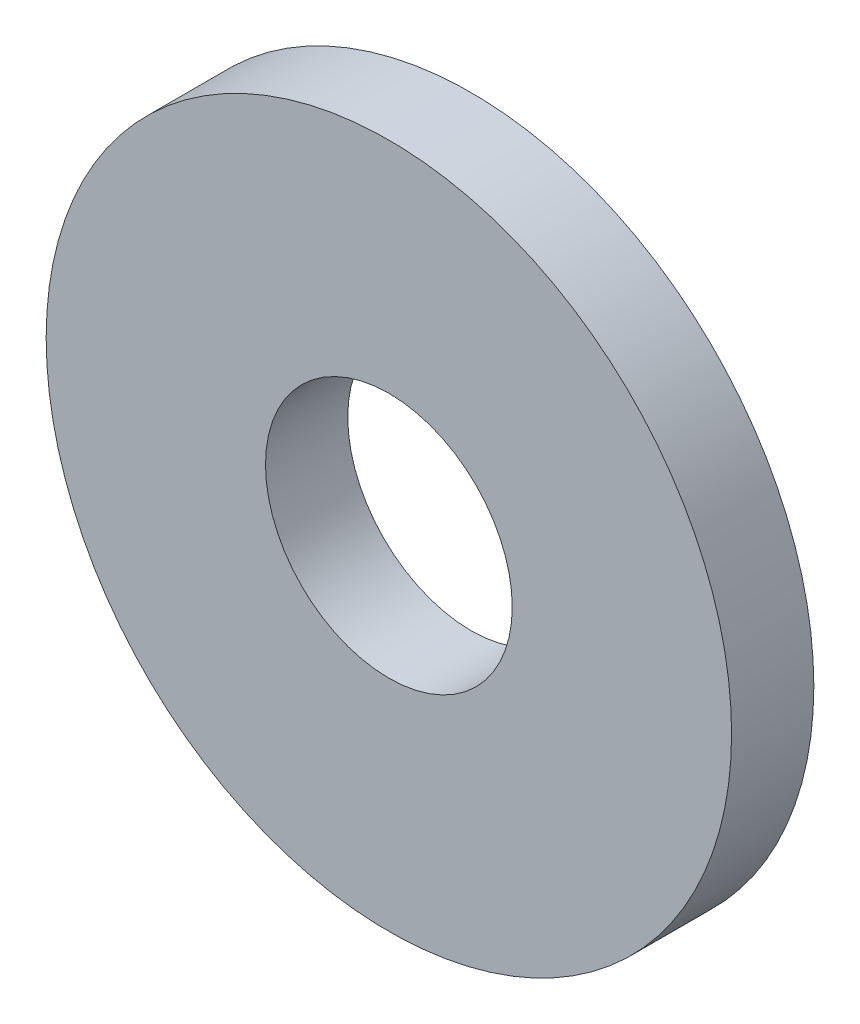
SolidWorks part; units mm, degrees
ref_plane "Front Plane" through (0, 0, 0) normal (0, 0, 1) x (1, 0, 0)
ref_plane "Top Plane" through (0, 0, 0) normal (0, 1, 0) x (1, 0, 0)
ref_plane "Right Plane" through (0, 0, 0) normal (1, 0, 0) x (0, 0, -1)
sketch "Sketch1" plane through (0, 0, 0) normal (0, 0, 1) x (1, 0, 0)
  circle A0 centre (0, 0) radius 5
  circle A1 centre (0, 0) radius 1.8
  dimension "OD" = 10
  dimension "ID1" = 3.6
extrude "Boss-Extrude1" add sketch "Sketch1" along normal blind 1.2
